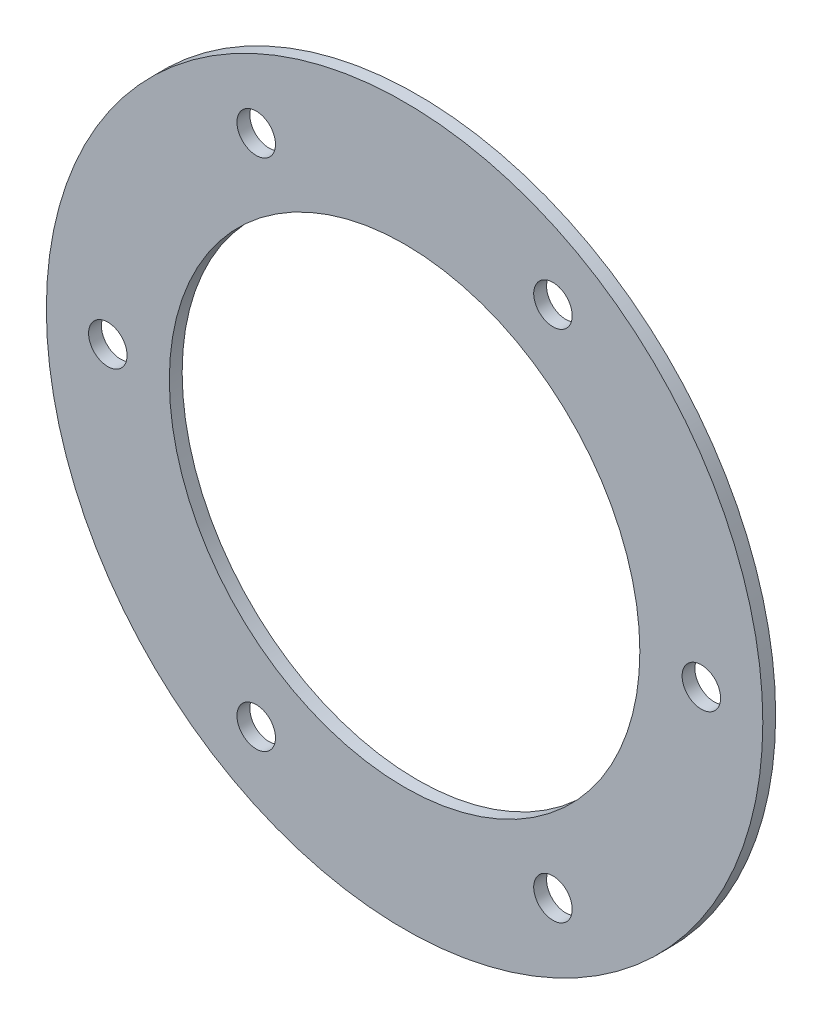
SolidWorks part; units mm, degrees
material "AISI 304"
ref_plane "Спереди" through (0, 0, 0) normal (0, 0, 1) x (1, 0, 0)
ref_plane "Сверху" through (0, 0, 0) normal (0, 1, 0) x (1, 0, 0)
ref_plane "Справа" through (0, 0, 0) normal (1, 0, 0) x (0, 0, -1)
sketch "Эскиз1" plane through (0, 0, 0) normal (0, 0, 1) x (1, 0, 0)
  circle A0 centre (0, 0) radius 110
  circle A1 centre (0, 0) radius 167.5
  dimension "D1" = 220
  dimension "D2" = 335
extrude "Бобышка-Вытянуть1" add sketch "Эскиз1" along normal blind 6
sketch "Эскиз2" plane through (0, 0, 6) normal (0, 0, 1) x (1, 0, 0)
  line L0 (0, 110) -> (0, 167.5) construction
  line L1 (0, 138.75) -> (0, 0) construction
  line L14 (0, 0) -> (-69.375, 120.161) construction
  circle A16 centre (0, 0) radius 110 construction
  circle A17 centre (0, 0) radius 167.5 construction
  circle A18 centre (0, 0) radius 138.75 construction
  circle A19 centre (-69.375, 120.161) radius 9
  circle A20 centre (69.375, 120.161) radius 9
  circle A21 centre (138.75, 0) radius 9
  circle A22 centre (69.375, -120.161) radius 9
  circle A23 centre (-69.375, -120.161) radius 9
  circle A24 centre (-138.75, 0) radius 9
  point P6 (0, 138.75)
  dimension "D1" = 30
  dimension "D2" = 18
extrude "Вырез-Вытянуть1" cut sketch "Эскиз2" against normal through all
